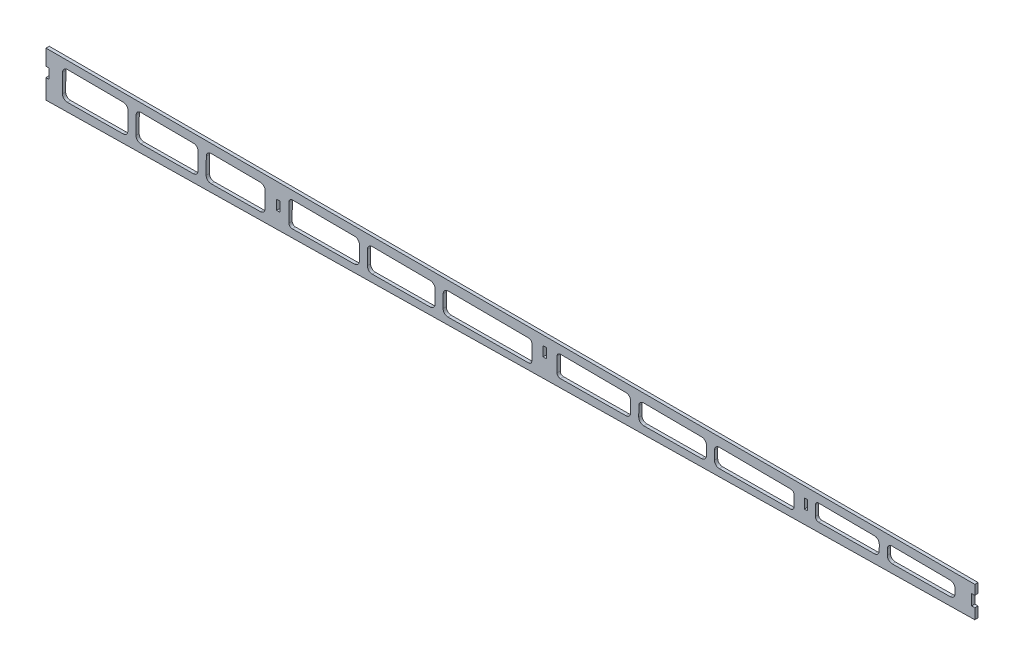
SolidWorks part; units mm, degrees
ref_plane "前视基准面" through (0, 0, 0) normal (0, 0, 1) x (1, 0, 0)
ref_plane "上视基准面" through (0, 0, 0) normal (0, 1, 0) x (1, 0, 0)
ref_plane "右视基准面" through (0, 0, 0) normal (1, 0, 0) x (0, 0, -1)
sketch "Model" plane through (0, 0, 0) normal (0, 0, 1) x (1, 0, 0)
  line L0 (586.2163, 41.7684) -> (586.2163, 35.8554)
  line L1 (584.2163, 35.8554) -> (584.2163, 29.1549)
  line L2 (584.2163, 29.1549) -> (586.2163, 29.1549)
  line L3 (153.779, 32.1444) -> (153.779, 26.1444)
  line L4 (318.8552, 33.15) -> (318.8552, 30.0955)
  line L5 (480.7142, 34.4585) -> (480.7142, 29.3765)
  line L6 (10.9715, 41.7684) -> (154.8752, 41.7684)
  line L7 (154.8752, 41.7684) -> (317.6526, 41.7684)
  line L8 (317.6526, 41.7684) -> (481.2107, 41.7684)
  line L9 (481.2107, 41.7684) -> (586.2163, 41.7684)
  line L10 (10.9715, 13.8422) -> (586.2163, 22.7505)
  line L11 (584.2163, 35.8554) -> (586.2163, 35.8554)
  line L12 (586.2163, 29.1549) -> (586.2163, 22.7505)
  line L13 (58.7572, 36.7017) -> (24.2578, 36.9107)
  line L14 (58.6999, 19.6377) -> (24.1973, 19.3166)
  line L15 (146.7481, 33.1685) -> (146.689, 23.4105)
  line L16 (21.2397, 33.9289) -> (21.1694, 22.3346)
  line L17 (69.7564, 36.635) -> (102.2558, 36.4381)
  line L18 (69.7001, 19.74) -> (102.2025, 20.0425)
  line L19 (113.2548, 36.3715) -> (143.7663, 36.1867)
  line L20 (113.2026, 20.1449) -> (143.7169, 20.4288)
  line L24 (163.5411, 36.6471) -> (202.0937, 36.4212)
  line L25 (213.0827, 36.3446) -> (248.9947, 36.0944)
  line L26 (259.9844, 36.0179) -> (309.947, 35.7386)
  line L27 (161.5272, 34.6611) -> (161.4469, 23.1264)
  line L28 (163.4655, 21.1126) -> (202.0383, 21.4421)
  line L29 (213.0365, 21.5448) -> (248.9446, 21.8799)
  line L30 (259.9386, 21.9825) -> (309.8865, 22.3787)
  line L31 (311.933, 33.7247) -> (311.8679, 24.3811)
  line L32 (329.5592, 36.8682) -> (370.1439, 36.5855)
  line L33 (381.1437, 36.5089) -> (417.0455, 36.2588)
  line L34 (428.0453, 36.1822) -> (472.3343, 35.8737)
  line L35 (329.5006, 23.7856) -> (370.1137, 24.1846)
  line L36 (381.1131, 24.2872) -> (417.0185, 24.6223)
  line L37 (428.0194, 24.725) -> (472.2921, 25.1383)
  line L38 (327.482, 25.7994) -> (327.5453, 34.8822)
  line L39 (474.3203, 33.8598) -> (474.2734, 27.1242)
  line L40 (489.4811, 36.9709) -> (524.0869, 36.7298)
  line L41 (535.0807, 36.6533) -> (570.9879, 36.4031)
  line L42 (489.4811, 26.7673) -> (524.0687, 27.0901)
  line L43 (535.0669, 27.1927) -> (570.975, 27.5279)
  line L44 (487.4673, 34.9849) -> (487.4625, 28.7687)
  line L45 (10.9715, 25.978) -> (10.9715, 13.8422)
  line L46 (318.8552, 33.15) -> (318.8552, 36.0955)
  line L47 (480.7142, 34.4585) -> (480.7142, 35.3765)
  line L48 (10.9715, 32.0068) -> (12.9715, 32.0068)
  line L49 (12.9715, 32.0068) -> (12.9715, 25.978)
  line L50 (12.9715, 25.978) -> (10.9715, 25.978)
  line L51 (10.9715, 41.7684) -> (10.9715, 32.0068)
  line L52 (153.779, 32.1444) -> (155.779, 32.1444)
  line L53 (155.779, 32.1444) -> (155.779, 26.1444)
  line L54 (155.779, 26.1444) -> (153.779, 26.1444)
  line L55 (318.8552, 36.0955) -> (320.8552, 36.0955)
  line L56 (320.8552, 36.0955) -> (320.8552, 30.0955)
  line L57 (320.8552, 30.0955) -> (318.8552, 30.0955)
  line L58 (480.7142, 35.3765) -> (482.7142, 35.3765)
  line L59 (482.7142, 35.3765) -> (482.7142, 29.3765)
  line L60 (482.7142, 29.3765) -> (480.7142, 29.3765)
  line L61 (573.9669, 33.3823) -> (573.9469, 30.5069)
  line L62 (532.0599, 33.6715) -> (532.0389, 30.2108)
  line L63 (527.0659, 33.709) -> (527.0406, 30.0691)
  line L64 (425.0245, 33.2004) -> (424.9914, 27.7431)
  line L65 (420.0246, 33.2407) -> (419.9904, 27.604)
  line L66 (378.1228, 33.5271) -> (378.0851, 27.3053)
  line L67 (373.1229, 33.5674) -> (373.0841, 27.1662)
  line L68 (256.9635, 33.0361) -> (256.9148, 25.0006)
  line L69 (251.9737, 33.0736) -> (251.9165, 24.8589)
  line L70 (210.0619, 33.3629) -> (210.0085, 24.5628)
  line L71 (205.0727, 33.4003) -> (205.0102, 24.4211)
  line L72 (110.2366, 33.3897) -> (110.1747, 23.1629)
  line L73 (105.2375, 33.42) -> (105.1746, 23.0242)
  line L74 (66.7382, 33.6532) -> (66.6722, 22.7581)
  line L75 (61.7389, 33.6835) -> (61.6719, 22.6194)
  arc A0 (58.6999, 19.6377) -> (61.6719, 22.6194) centre (58.672, 22.6375) ccw
  arc A1 (143.7169, 20.4288) -> (146.689, 23.4105) centre (143.689, 23.4287) ccw
  arc A2 (21.1694, 22.3346) -> (24.1973, 19.3166) centre (24.1694, 22.3165) ccw
  arc A3 (146.7481, 33.1685) -> (143.7663, 36.1867) centre (143.7481, 33.1867) ccw
  arc A4 (24.2578, 36.9107) -> (21.2397, 33.9289) centre (24.2396, 33.9107) ccw
  arc A5 (61.7389, 33.6835) -> (58.7572, 36.7017) centre (58.739, 33.7017) ccw
  arc A6 (69.7564, 36.635) -> (66.7382, 33.6532) centre (69.7382, 33.6351) ccw
  arc A7 (102.2025, 20.0425) -> (105.1746, 23.0242) centre (102.1746, 23.0424) ccw
  arc A8 (105.2375, 33.42) -> (102.2558, 36.4381) centre (102.2376, 33.4382) ccw
  arc A9 (66.6722, 22.7581) -> (69.7001, 19.74) centre (69.6722, 22.7399) ccw
  arc A10 (113.2548, 36.3715) -> (110.2366, 33.3897) centre (113.2366, 33.3716) ccw
  arc A11 (110.1747, 23.1629) -> (113.2026, 20.1449) centre (113.1746, 23.1447) ccw
  arc A12 (163.5411, 36.6471) -> (161.5272, 34.6611) centre (163.5272, 34.6472) ccw
  arc A13 (161.4469, 23.1264) -> (163.4655, 21.1126) centre (163.4468, 23.1125) ccw
  arc A14 (309.8865, 22.3787) -> (311.8679, 24.3811) centre (309.8679, 24.3786) ccw
  arc A15 (205.0727, 33.4003) -> (202.0937, 36.4212) centre (202.0728, 33.4212) ccw
  arc A16 (202.0383, 21.4421) -> (205.0102, 24.4211) centre (202.0103, 24.442) ccw
  arc A17 (213.0827, 36.3446) -> (210.0619, 33.3629) centre (213.0618, 33.3447) ccw
  arc A18 (210.0085, 24.5628) -> (213.0365, 21.5448) centre (213.0085, 24.5446) ccw
  arc A19 (251.9737, 33.0736) -> (248.9947, 36.0944) centre (248.9738, 33.0945) ccw
  arc A20 (248.9446, 21.8799) -> (251.9165, 24.8589) centre (248.9166, 24.8798) ccw
  arc A21 (259.9844, 36.0179) -> (256.9635, 33.0361) centre (259.9635, 33.018) ccw
  arc A22 (256.9148, 25.0006) -> (259.9386, 21.9825) centre (259.9148, 24.9825) ccw
  arc A23 (311.933, 33.7247) -> (309.947, 35.7386) centre (309.9331, 33.7386) ccw
  arc A24 (474.3203, 33.8598) -> (472.3343, 35.8737) centre (472.3204, 33.8737) ccw
  arc A25 (329.5592, 36.8682) -> (327.5453, 34.8822) centre (329.5452, 34.8683) ccw
  arc A26 (327.482, 25.7994) -> (329.5006, 23.7856) centre (329.482, 25.7855) ccw
  arc A27 (472.2921, 25.1383) -> (474.2734, 27.1242) centre (472.2734, 27.1382) ccw
  arc A28 (373.1229, 33.5674) -> (370.1439, 36.5855) centre (370.123, 33.5856) ccw
  arc A29 (370.1137, 24.1846) -> (373.0841, 27.1662) centre (370.0842, 27.1844) ccw
  arc A30 (381.1437, 36.5089) -> (378.1228, 33.5271) centre (381.1228, 33.509) ccw
  arc A31 (378.0851, 27.3053) -> (381.1131, 24.2872) centre (381.0851, 27.2871) ccw
  arc A32 (417.0185, 24.6223) -> (419.9904, 27.604) centre (416.9905, 27.6222) ccw
  arc A33 (420.0246, 33.2407) -> (417.0455, 36.2588) centre (417.0246, 33.2589) ccw
  arc A34 (428.0453, 36.1822) -> (425.0245, 33.2004) centre (428.0245, 33.1823) ccw
  arc A35 (424.9914, 27.7431) -> (428.0194, 24.725) centre (427.9914, 27.7249) ccw
  arc A36 (489.4811, 36.9709) -> (487.4673, 34.9849) centre (489.4672, 34.971) ccw
  arc A37 (487.4625, 28.7687) -> (489.4811, 26.7673) centre (489.4625, 28.7672) ccw
  arc A38 (527.0659, 33.709) -> (524.0869, 36.7298) centre (524.066, 33.7299) ccw
  arc A39 (524.0687, 27.0901) -> (527.0406, 30.0691) centre (524.0407, 30.0899) ccw
  arc A40 (535.0807, 36.6533) -> (532.0599, 33.6715) centre (535.0598, 33.6533) ccw
  arc A41 (532.0389, 30.2108) -> (535.0669, 27.1927) centre (535.0389, 30.1926) ccw
  arc A42 (570.975, 27.5279) -> (573.9469, 30.5069) centre (570.947, 30.5278) ccw
  arc A43 (573.9669, 33.3823) -> (570.9879, 36.4031) centre (570.967, 33.4032) ccw
extrude "凸台-拉伸1" add sketch "Model" along normal blind 2
